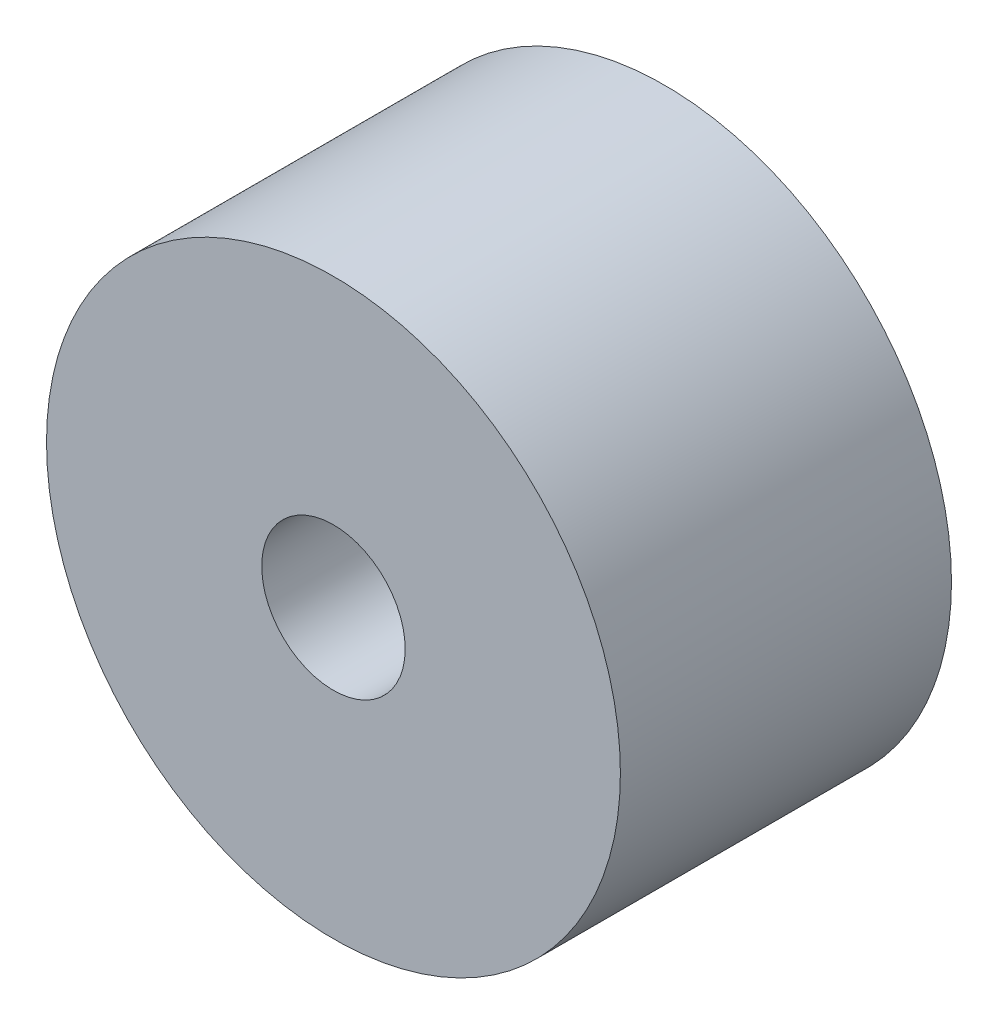
SolidWorks part; units mm, degrees
ref_plane "Front Plane" through (0, 0, 0) normal (0, 0, 1) x (1, 0, 0)
ref_plane "Top Plane" through (0, 0, 0) normal (0, 1, 0) x (1, 0, 0)
ref_plane "Right Plane" through (0, 0, 0) normal (1, 0, 0) x (0, 0, -1)
sketch "S01 - Swaged end stop" plane through (0, 0, 0) normal (0, 0, 1) x (1, 0, 0)
  circle A0 centre (0, 0) radius 2.6
  circle A1 centre (0, 0) radius 0.65
  dimension "D1" = 1.3
  dimension "D2" = 5.2
extrude "01 - Swaged end stop" add sketch "S01 - Swaged end stop" along normal blind 3
